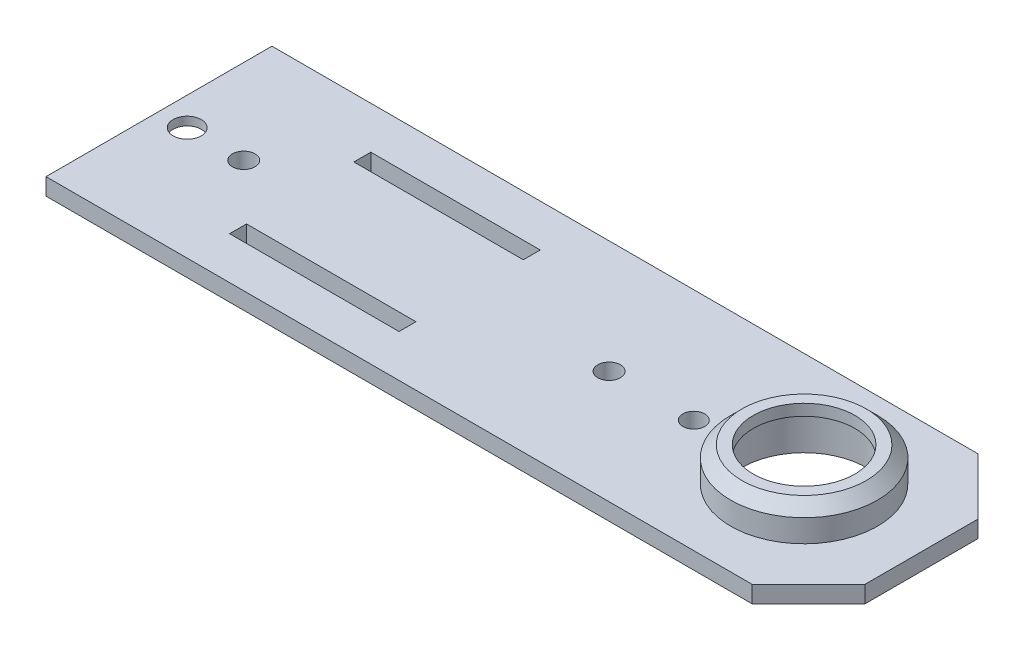
SolidWorks part; units mm, degrees
ref_plane "Alzado" through (0, 0, 0) normal (0, 0, 1) x (1, 0, 0)
ref_plane "Planta" through (0, 0, 0) normal (0, 1, 0) x (1, 0, 0)
ref_plane "Vista lateral" through (0, 0, 0) normal (1, 0, 0) x (0, 0, -1)
sketch "Croquis1" plane through (0, 0, 0) normal (0, 1, 0) x (1, 0, 0)
  line L1 (-67.5, -20) -> (67.5, -20)
  line L2 (-67.5, -20) -> (-67.5, -10)
  line L3 (-67.5, 20) -> (67.5, 20)
  line L4 (67.5, -20) -> (67.5, 20)
  line L5 (-67.5, -20) -> (67.5, 20) construction
  line L6 (-67.5, 20) -> (67.5, -20) construction
  line L9 (-67.5, 10) -> (-67.5, 20)
  line L10 (-67.5, -10) -> (-57.5, -10)
  line L11 (-42.5, 9.5) -> (-12.5, 9.5)
  line L12 (-42.5, 9.5) -> (-42.5, 12.5)
  line L13 (-42.5, 12.5) -> (-12.5, 12.5)
  line L14 (-12.5, 9.5) -> (-12.5, 12.5)
  line L15 (-42.5, 9.5) -> (-12.5, 12.5) construction
  line L16 (-42.5, 12.5) -> (-12.5, 9.5) construction
  line L17 (-42.5, -12.5) -> (-12.5, -12.5)
  line L18 (-42.5, -12.5) -> (-42.5, -9.5)
  line L19 (-42.5, -9.5) -> (-12.5, -9.5)
  line L20 (-12.5, -12.5) -> (-12.5, -9.5)
  line L21 (-42.5, -12.5) -> (-12.5, -9.5) construction
  line L22 (-42.5, -9.5) -> (-12.5, -12.5) construction
  line L24 (-57.5, 10) -> (-67.5, 10)
  line L25 (-57.5, -10) -> (-57.5, 10)
  circle A2 centre (46.714, 0) radius 11
  circle A3 centre (-52.5, 0) radius 2
  circle A4 centre (27.1858, 0) radius 1.9377
  circle A5 centre (12.1858, 0) radius 2
  point P0 (0, 0)
  point P20 (-27.5, 11)
  point P28 (-27.5, -11)
  dimension "D6" = 15
  dimension "D7" = 22
  dimension "D11" = 10
  dimension "D12" = 4
  dimension "D1" = 40
  dimension "D2" = 135
  dimension "D3" = 10
  dimension "D4" = 20
  dimension "D8" = 30
  dimension "D9" = 3
  dimension "D10" = 40
  dimension "D13" = 12.5
  dimension "D14" = 12.5
extrude "Saliente-Extruir1" add sketch "Croquis1" along normal blind 3
sketch "Croquis2" plane through (0, 3, 0) normal (0, 1, 0) x (1, 0, 0)
  circle A0 centre (46.714, 0) radius 11
  circle A1 centre (46.714, 0) radius 13
  dimension "D1" = 2
extrude "Saliente-Extruir2" add sketch "Croquis2" along normal blind 4
sketch "Croquis3" plane through (0, 7, 0) normal (0, 1, 0) x (1, 0, 0)
  circle A0 centre (46.714, 0) radius 13
  circle A1 centre (46.714, 0) radius 9
  dimension "D1" = 18
extrude "Saliente-Extruir3" add sketch "Croquis3" along normal blind 2
chamfer "Chaflán1" distance 2 angle 45 1 edges at (46.714, 9, 13)
chamfer "Chaflán2" distance 10 angle 45 2 edges at (67.5, 1.5, -20) (67.5, 1.5, 20)
sketch "Croquis4" plane through (0, 3, 0) normal (0, 1, 0) x (1, 0, 0)
  line L0 (-57.5, 0) -> (-67.5, 0) construction
  line L5 (-67.5, 10) -> (-57.5, 10)
  line L6 (-67.5, 10) -> (-67.5, -10)
  line L7 (-67.5, -10) -> (-57.5, -10)
  line L8 (-57.5, 10) -> (-57.5, -10)
  circle A0 centre (-62.5, 0) radius 2.5
  dimension "D1" = 5
extrude "Saliente-Extruir4" add sketch "Croquis4" against normal blind 1.5
